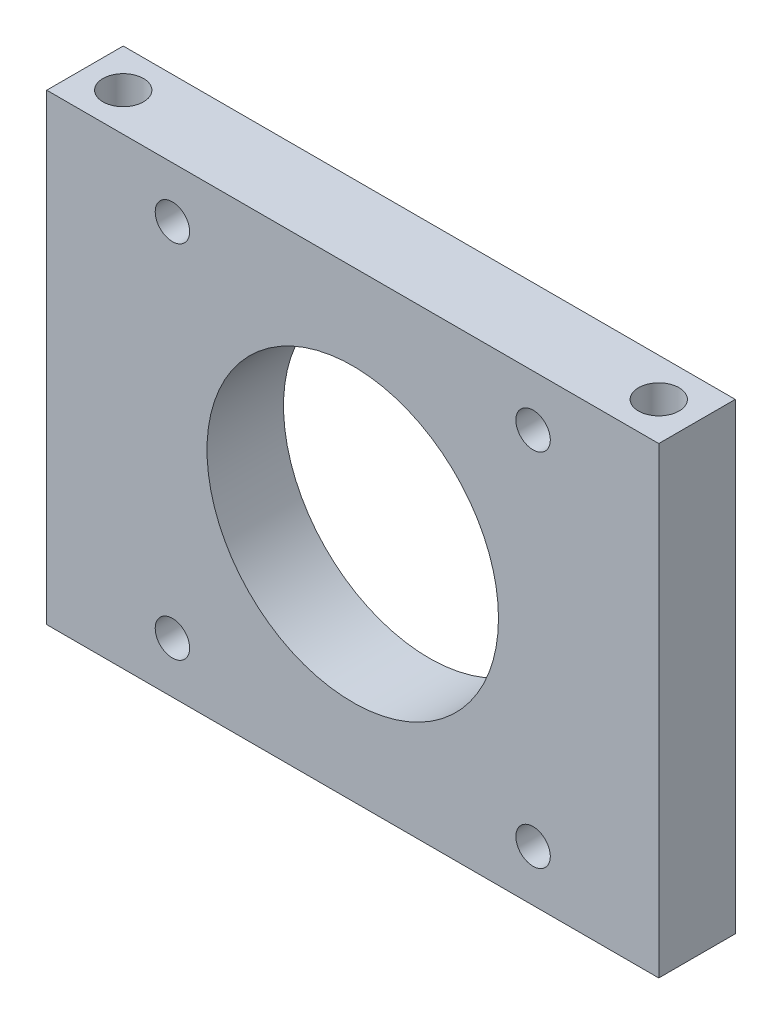
SolidWorks part; units mm, degrees
material "6061 合金"
ref_plane "前基準面" through (0, 0, 0) normal (0, 0, 1) x (1, 0, 0)
ref_plane "上基準面" through (0, 0, 0) normal (0, 1, 0) x (1, 0, 0)
ref_plane "右基準面" through (0, 0, 0) normal (1, 0, 0) x (0, 0, -1)
sketch "草圖1" plane through (0, 0, 0) normal (0, 0, 1) x (1, 0, 0)
  line L1 (-40, -30.25) -> (40, -30.25)
  line L2 (-40, -30.25) -> (-40, 30.25)
  line L3 (-40, 30.25) -> (40, 30.25)
  line L4 (40, -30.25) -> (40, 30.25)
  line L5 (-40, -30.25) -> (40, 30.25) construction
  line L6 (-40, 30.25) -> (40, -30.25) construction
  point P0 (0, 0)
  dimension "D1" = 60.5
  dimension "D2" = 80
extrude "填料-伸長1" add sketch "草圖1" along normal mid plane 10
sketch "草圖3" plane through (0, 0, 5) normal (0, 0, 1) x (1, 0, 0)
  circle A0 centre (0, 0) radius 19.05
  dimension "D1" = 38.1
extrude "除料-伸長1" cut sketch "草圖3" against normal through all
sketch "草圖9" plane through (0, -30.25, 0) normal (0, -1, 0) x (1, 0, 0)
  line L1 (-40, -5) -> (40, -5)
  line L2 (-40, -5) -> (-40, 5)
  line L3 (-40, 5) -> (40, 5)
  line L4 (40, -5) -> (40, 5)
  line L5 (-40, -5) -> (40, 5) construction
  line L6 (-40, 5) -> (40, -5) construction
  point P0 (0, 0)
extrude "填料-伸長3" [suppressed] add sketch "草圖9" along normal blind 25
hole_wizard "M4 餘隙孔1" positions "草圖6" profile "草圖7" hole size "M4" standard "Ansi Metric" end condition through all
sketch "草圖6" plane through (0, 0, -5) normal (0, 0, -1) x (-1, 0, 0)
  line L1 (-23.57, -23.57) -> (23.57, -23.57) construction
  line L2 (-23.57, -23.57) -> (-23.57, 23.57) construction
  line L3 (-23.57, 23.57) -> (23.57, 23.57) construction
  line L4 (23.57, -23.57) -> (23.57, 23.57) construction
  line L5 (-23.57, -23.57) -> (23.57, 23.57) construction
  line L6 (-23.57, 23.57) -> (23.57, -23.57) construction
  point P1 (23.57, 23.57)
  point P36 (-23.57, -23.57)
  point P37 (-23.57, 23.57)
  point P38 (23.57, -23.57)
  dimension "D1" = 47.14
  dimension "D2" = 47.14
sketch "草圖7" plane through (-23.57, 23.57, -5) normal (1, 0, 0) x (0, 1, 0)
  line L0 (0, 0) -> (0, 10)
  line L1 (0, 10) -> (2.25, 10)
  line L2 (2.25, 10) -> (2.25, 0)
  line L5 (2.25, 0) -> (0, 0)
  line L11 (0, -6.35) -> (0, 107.95) construction
  dimension "貫穿孔直徑" = 4.5
  dimension "貫穿孔深度" = 10
hole_wizard "M5 餘隙孔1" positions "草圖4" profile "草圖5" hole size "M5" standard "Ansi Metric" end condition through all
sketch "草圖4" plane through (0, 30.25, 0) normal (0, 1, 0) x (1, 0, 0)
  line L0 (-35, 0) -> (35, 0) construction
  point P0 (-35, 0)
  point P1 (35, 0)
  dimension "D1" = 70
sketch "草圖5" plane through (-35, 30.25, 0) normal (1, 0, 0) x (0, 0, 1)
  line L0 (0, 0) -> (0, 60.5)
  line L1 (0, 60.5) -> (2.65, 60.5)
  line L2 (2.65, 60.5) -> (2.65, 0)
  line L5 (2.65, 0) -> (0, 0)
  line L11 (0, -6.35) -> (0, 107.95) construction
  dimension "貫穿孔直徑" = 5.3
  dimension "貫穿孔深度" = 60.5
